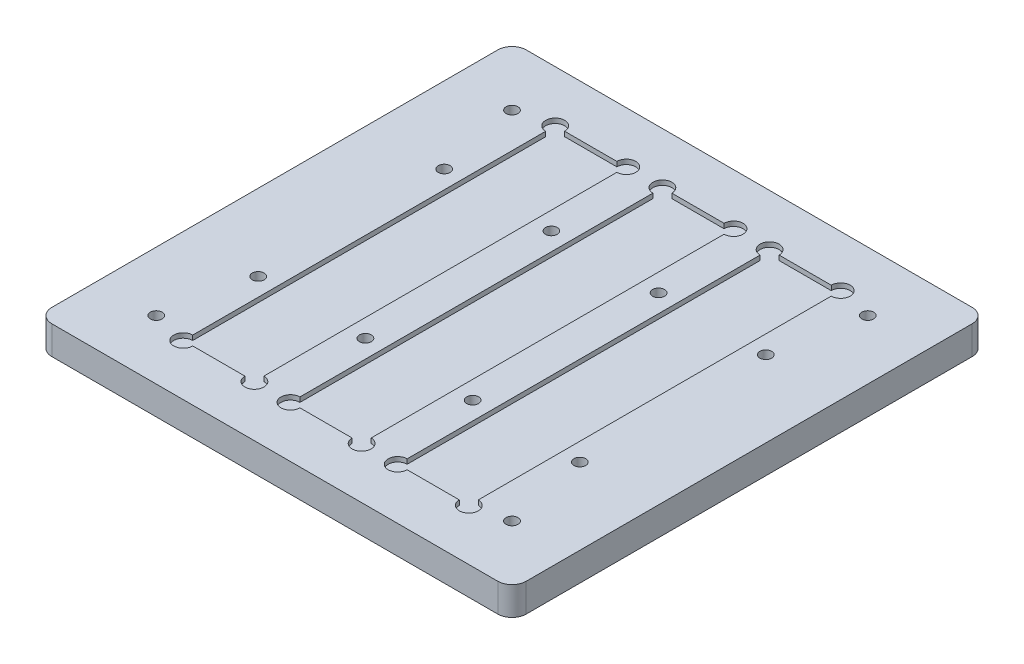
SolidWorks part; units mm, degrees
ref_plane "Front Plane" through (0, 0, 0) normal (0, 0, 1) x (1, 0, 0)
ref_plane "Top Plane" through (0, 0, 0) normal (0, 1, 0) x (1, 0, 0)
ref_plane "Right Plane" through (0, 0, 0) normal (1, 0, 0) x (0, 0, -1)
sketch "Sketch1" plane through (0, 0, 0) normal (0, 1, 0) x (1, 0, 0)
  line L0 (0, 50) -> (0, 0) construction
  line L1 (-50, -50) -> (50, -50)
  line L2 (-50, -50) -> (-50, 50)
  line L3 (-50, 50) -> (50, 50)
  line L4 (50, -50) -> (50, 50)
  line L5 (-50, -50) -> (50, 50) construction
  line L6 (-50, 50) -> (50, -50) construction
  line L7 (0, 0) -> (50, 0) construction
  circle A0 centre (-37.5, 37.5) radius 1.25 construction
  circle A1 centre (37.5, 37.5) radius 1.25 construction
  circle A2 centre (37.5, -37.5) radius 1.25 construction
  circle A3 centre (-37.5, -37.5) radius 1.25 construction
  point P0 (0, 0)
  dimension "D2" = 75
  dimension "D3" = 75
  dimension "D4" = 2.5
  dimension "D1" = 100
extrude "Boss-Extrude1" add sketch "Sketch1" along normal blind 6
sketch "Sketch2" plane through (0, 6, 0) normal (0, 1, 0) x (1, 0, 0)
  line L0 (-7.3, 39) -> (7.3, 39) construction
  line L1 (-29.9, 39) -> (-15.3, 39) construction
  line L2 (-29.9, 39) -> (-29.9, -39) construction
  line L3 (-29.9, -39) -> (-15.3, -39) construction
  line L4 (-15.3, 39) -> (-15.3, -39) construction
  line L5 (-7.3, 39) -> (-7.3, -39) construction
  line L6 (-7.3, -39) -> (7.3, -39) construction
  line L7 (7.3, 39) -> (7.3, -39) construction
  line L8 (15.3, 39) -> (29.9, 39) construction
  line L9 (15.3, 39) -> (15.3, -39) construction
  line L10 (15.3, -39) -> (29.9, -39) construction
  line L11 (29.9, 39) -> (29.9, -39) construction
  line L12 (0, 39) -> (0, 0) construction
  line L13 (0, 0) -> (7.3, 0) construction
  line L14 (-30.1, 39.2) -> (-30.1, -39.2)
  line L15 (-30.1, -39.2) -> (-15.1, -39.2)
  line L16 (-15.1, 39.2) -> (-15.1, -39.2)
  line L17 (-30.1, 39.2) -> (-15.1, 39.2)
  line L18 (-7.5, 39.2) -> (7.5, 39.2)
  line L19 (7.5, 39.2) -> (7.5, -39.2)
  line L20 (-7.5, -39.2) -> (7.5, -39.2)
  line L21 (-7.5, 39.2) -> (-7.5, -39.2)
  line L22 (15.1, 39.2) -> (15.1, -39.2)
  line L23 (15.1, -39.2) -> (30.1, -39.2)
  line L24 (30.1, 39.2) -> (30.1, -39.2)
  line L25 (15.1, 39.2) -> (30.1, 39.2)
  dimension "D1" = 14.6
  dimension "D2" = 78
  dimension "D4" = 8
  dimension "D5" = 0.2
  dimension "D6" = 0.2
  dimension "D7" = 0.2
  dimension "D3" = 3
extrude "Cut-Extrude1" cut sketch "Sketch2" against normal blind 1
sketch "Sketch3" plane through (0, 6, 0) normal (0, 1, 0) x (1, 0, 0)
  line L1 (-37.5, 34.3246) -> (-34.75, 35.9123)
  line L2 (-34.75, 35.9123) -> (-34.75, 39.0877)
  line L3 (-34.75, 39.0877) -> (-37.5, 40.6754)
  line L4 (-37.5, 40.6754) -> (-40.25, 39.0877)
  line L5 (-40.25, 39.0877) -> (-40.25, 35.9123)
  line L6 (-40.25, 35.9123) -> (-37.5, 34.3246)
  line L7 (37.5, 34.3246) -> (40.25, 35.9123)
  line L8 (40.25, 35.9123) -> (40.25, 39.0877)
  line L9 (40.25, 39.0877) -> (37.5, 40.6754)
  line L10 (37.5, 40.6754) -> (34.75, 39.0877)
  line L11 (34.75, 39.0877) -> (34.75, 35.9123)
  line L12 (34.75, 35.9123) -> (37.5, 34.3246)
  line L13 (37.5, -34.3246) -> (34.75, -35.9123)
  line L14 (34.75, -35.9123) -> (34.75, -39.0877)
  line L15 (34.75, -39.0877) -> (37.5, -40.6754)
  line L16 (37.5, -40.6754) -> (40.25, -39.0877)
  line L17 (40.25, -39.0877) -> (40.25, -35.9123)
  line L18 (40.25, -35.9123) -> (37.5, -34.3246)
  line L19 (-37.5, -34.3246) -> (-40.25, -35.9123)
  line L20 (-40.25, -35.9123) -> (-40.25, -39.0877)
  line L21 (-40.25, -39.0877) -> (-37.5, -40.6754)
  line L22 (-37.5, -40.6754) -> (-34.75, -39.0877)
  line L23 (-34.75, -39.0877) -> (-34.75, -35.9123)
  line L24 (-34.75, -35.9123) -> (-37.5, -34.3246)
  circle A0 centre (-37.5, 37.5) radius 2.75 construction
  circle A1 centre (37.5, 37.5) radius 2.75 construction
  circle A2 centre (37.5, -37.5) radius 2.75 construction
  circle A3 centre (-37.5, -37.5) radius 2.75 construction
  dimension "D1" = 5.5
sketch "Sketch4" plane through (0, 6, 0) normal (0, 1, 0) x (1, 0, 0)
  line L0 (-22.6, 39.2) -> (-22.6, 24.6779) construction
  line L1 (0, 0) -> (0, 14.1041) construction
  line L2 (-15.1, 39.2) -> (-7.5, -39.2) construction
  line L3 (-15.1, 39.2) -> (-30.1, 39.2) construction
  line L4 (-15.1, 0) -> (-30.1, 39.2) construction
  line L5 (-15.1, -39.2) -> (-15.1, 39.2) construction
  line L6 (-22.6, 19.6) -> (-11.3, 19.6) construction
  line L7 (-11.3, 0) -> (0, 0) construction
  line L8 (-11.3, 0) -> (-11.3, 19.6) construction
  circle A0 centre (-11.3, 19.6) radius 1.5
  circle A1 centre (11.3, 19.6) radius 1.5
  circle A4 centre (-33.9, 19.6) radius 1.5
  circle A5 centre (33.9, 19.6) radius 1.5
  circle A6 centre (33.9, -19.6) radius 1.5
  circle A7 centre (11.3, -19.6) radius 1.5
  circle A8 centre (-33.9, -19.6) radius 1.5
  circle A9 centre (-11.3, -19.6) radius 1.5
  dimension "D1" = 3
hole_wizard "M3 Tapped Hole1" positions "Sketch5" profile "Sketch6" tap size "M3" standard "ISO"
sketch "Sketch5" plane through (0, 6, 0) normal (0, 1, 0) x (1, 0, 0)
  point P4 (11.3, 19.6)
  point P7 (-33.9, 19.6)
  point P10 (33.9, 19.6)
  point P14 (-37.5, 37.5)
  point P17 (37.5, 37.5)
  point P20 (37.5, -37.5)
  point P23 (-37.5, -37.5)
  point P27 (-33.9, -19.6)
  point P30 (-11.3, -19.6)
  point P33 (11.3, -19.6)
  point P36 (33.9, -19.6)
  point P39 (-11.3, 19.6)
sketch "Sketch6" plane through (11.3, 6, -19.6) normal (1, 0, 0) x (0, 0, 1)
  line L0 (0, 0) -> (0, 4.7511)
  line L1 (0, 4.7511) -> (1.25, 4)
  line L2 (1.25, 4) -> (1.25, 0)
  line L5 (1.25, 0) -> (0, 0)
  line L10 (0, 4.7511) -> (-1.25, 4) construction
  line L11 (0, -6.35) -> (0, 107.95) construction
  dimension "Tap Drill Dia." = 2.5
  dimension "Tap Drill Depth" = 4
  dimension "Drill Angle" = 118
cosmetic thread "Hole Thread1" parameters "D1"=4, "D2"=3
cosmetic thread "Hole Thread2" parameters "D1"=4, "D2"=3
cosmetic thread "Hole Thread3" parameters "D1"=4, "D2"=3
cosmetic thread "Hole Thread4" parameters "D1"=4, "D2"=3
cosmetic thread "Hole Thread5" parameters "D1"=4, "D2"=3
cosmetic thread "Hole Thread6" parameters "D1"=4, "D2"=3
cosmetic thread "Hole Thread7" parameters "D1"=4, "D2"=3
cosmetic thread "Hole Thread8" parameters "D1"=4, "D2"=3
cosmetic thread "Hole Thread9" parameters "D1"=4, "D2"=3
cosmetic thread "Hole Thread10" parameters "D1"=4, "D2"=3
cosmetic thread "Hole Thread11" parameters "D1"=4, "D2"=3
cosmetic thread "Hole Thread12" parameters "D1"=4, "D2"=3
sketch "Sketch11" plane through (0, 6, 0) normal (0, 1, 0) x (1, 0, 0)
  line L2 (30.1, -39.2) -> (30.1, 39.2) construction
  line L14 (-7.5, 39.2) -> (-7.5, -39.2) construction
  line L15 (-7.5, 39.2) -> (-7.5, -39.2) construction
  line L16 (7.5, 39.2) -> (-7.5, 39.2) construction
  line L17 (7.5, -39.2) -> (7.5, 39.2) construction
  line L18 (7.5, -39.2) -> (7.5, 39.2) construction
  line L20 (30.1, 39.2) -> (15.1, 39.2) construction
  line L21 (15.1, -39.2) -> (30.1, -39.2) construction
  line L24 (-30.1, -39.2) -> (-15.1, -39.2) construction
  line L25 (-15.1, -39.2) -> (-15.1, 39.2) construction
  line L27 (15.1, -39.2) -> (30.1, -39.2) construction
  line L28 (15.1, 39.2) -> (15.1, -39.2) construction
  circle A0 centre (-30.1, 39.2) radius 2
  circle A5 centre (-30.1, -39.2) radius 2
  circle A6 centre (-15.1, -39.2) radius 2
  circle A7 centre (-7.5, -39.2) radius 2
  circle A8 centre (7.5, -39.2) radius 2
  circle A9 centre (15.1, -39.2) radius 2
  circle A10 centre (30.1, -39.2) radius 2
  circle A11 centre (30.1, 39.2) radius 2
  circle A12 centre (7.5, 39.2) radius 2
  circle A13 centre (15.1, 39.2) radius 2
  circle A14 centre (-7.5, 39.2) radius 2
  circle A15 centre (-15.1, 39.2) radius 2
  dimension "D1" = 4
extrude "Cut-Extrude3" cut sketch "Sketch11" against normal up to surface (1 mm away) up to face at (-22.6, 5, 0)
fillet "Fillet1" [suppressed] radius 3
fillet "Fillet2" radius 3 4 edges at (50, 3, 50) (-50, 3, 50) (50, 3, -50) (-50, 3, -50)
